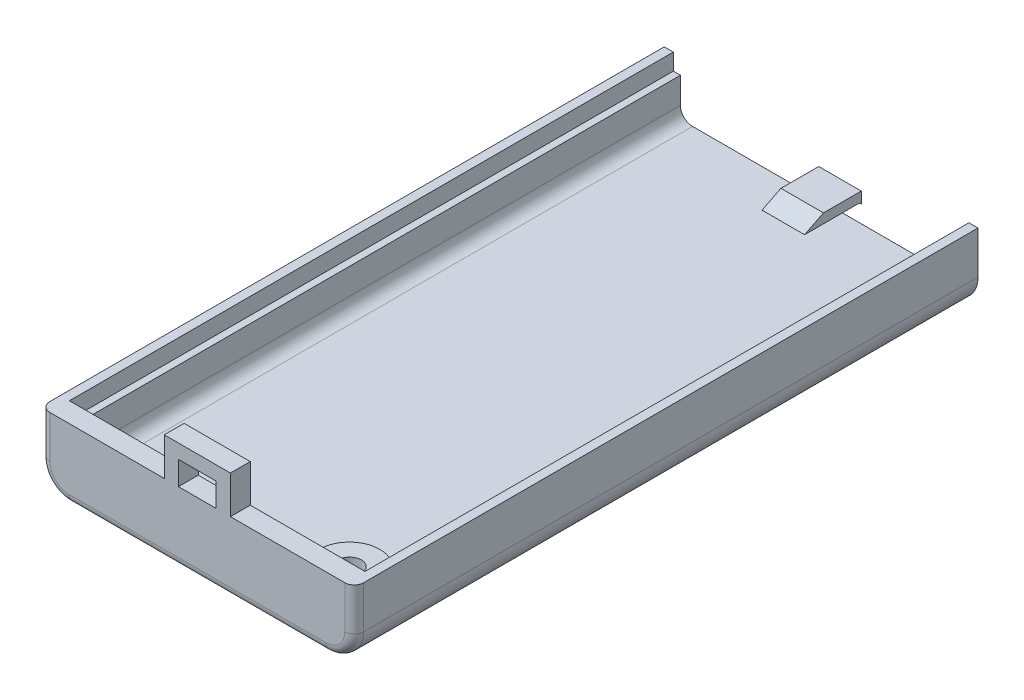
SolidWorks part; units mm, degrees
ref_plane "Plan de face" through (0, 0, 0) normal (0, 0, 1) x (1, 0, 0)
ref_plane "Plan de dessus" through (0, 0, 0) normal (0, 1, 0) x (1, 0, 0)
ref_plane "Plan de droite" through (0, 0, 0) normal (1, 0, 0) x (0, 0, -1)
sketch "Esquisse1" plane through (0, 0, 0) normal (0, 0, 1) x (1, 0, 0)
  line L0 (0, 15.2923) -> (0, -18.7385) construction
  line L1 (-13.6, -7.5) -> (13.6, -7.5)
  line L2 (-16.6, -4.5) -> (-16.6, 0)
  line L3 (16.6, -4.5) -> (16.6, 0)
  arc A0 (16.6, -4.5) -> (13.6, -7.5) centre (13.6, -4.5) cw
  arc A1 (-13.6, -7.5) -> (-16.6, -4.5) centre (-13.6, -4.5) cw
  point P3 (-16.6, -2.25)
  point P12 (16.6, -2.25)
  dimension "D3" = 3
  dimension "D1" = 16.6
  dimension "D2" = 7.5
  dimension "D4" = 16.6
extrude "Extru.-Mince1" add sketch "Esquisse1" along normal blind 32 and the other way blind 32 thin thin type one direction reverse wall 1.71
sketch "Esquisse2" plane through (0, 0, 32) normal (0, 0, 1) x (1, 0, 0)
  line L0 (16.6, -4.5) -> (16.6, 0) construction
  line L1 (-13.6, -7.5) -> (13.6, -7.5) construction
  line L2 (-16.6, 0) -> (-16.6, -4.5) construction
  line L3 (16.6, -4.5) -> (16.6, 0)
  line L4 (-13.6, -7.5) -> (13.6, -7.5)
  line L5 (-16.6, 0) -> (-16.6, -4.5)
  line L6 (-16.6, 0) -> (-3.5, 0)
  line L7 (0, 5.1948) -> (0, -16.7122) construction
  line L9 (-2, 0) -> (2, 0)
  line L10 (-2, 0) -> (-2, 2.5)
  line L11 (3.5, 0) -> (16.6, 0)
  line L12 (-3.5, 0) -> (-3.5, 4)
  line L13 (-3.5, 4) -> (3.5, 4)
  line L14 (3.5, 4) -> (3.5, 0)
  line L15 (-2, 2.5) -> (2, 2.5)
  line L16 (2, 0) -> (2, 2.5)
  arc A0 (13.6, -7.5) -> (16.6, -4.5) centre (13.6, -4.5) ccw construction
  arc A1 (-16.6, -4.5) -> (-13.6, -7.5) centre (-13.6, -4.5) ccw construction
  arc A2 (13.6, -7.5) -> (16.6, -4.5) centre (13.6, -4.5) ccw
  arc A3 (-16.6, -4.5) -> (-13.6, -7.5) centre (-13.6, -4.5) ccw
  dimension "D1" = 7
  dimension "D2" = 4
  dimension "D3" = 4
  dimension "D4" = 2.5
extrude "Boss.-Extru.1" add sketch "Esquisse2" along normal blind 2 and the other way blind 0.1
sketch "Esquisse3" plane through (0, 0, 0) normal (0, 1, 0) x (1, 0, 0)
  line L0 (0, -38.3609) -> (0, 35.8081) construction
  line L1 (-15.64, -31.9) -> (15.64, -31.9)
  line L2 (-15.64, -31.9) -> (-15.64, 34)
  line L3 (-15.64, 34) -> (15.64, 34)
  line L4 (15.64, -31.9) -> (15.64, 34)
  line L6 (14.89, -31.9) -> (3.5, -31.9) construction
  line L7 (-14.89, 32) -> (-14.89, -31.9) construction
  dimension "D1" = 34
  dimension "D2" = 0.75
extrude "Enlèv. mat.-Extru.4" cut sketch "Esquisse3" against normal blind 1.75
sketch "Esquisse4" plane through (0, -5.79, 0) normal (0, 1, 0) x (1, 0, 0)
  line L0 (0, -7.689) -> (0, 39.4106) construction
  line L1 (-13.6, 32) -> (13.6, 32) construction
  line L2 (-2.25, 28) -> (2.25, 28)
  line L3 (-2.25, 28) -> (-2.25, 34)
  line L4 (-2.25, 34) -> (2.25, 34)
  line L5 (2.25, 28) -> (2.25, 34)
  dimension "D1" = 2
  dimension "D2" = 6
  dimension "D3" = 4.5
extrude "Boss.-Extru.2" add sketch "Esquisse4" along normal blind 1
sketch "Esquisse5" plane through (0, 0, 0) normal (1, 0, 0) x (0, 0, -1)
  line L0 (34, -5.79) -> (34, -5.99)
  line L1 (34, -5.99) -> (33.8, -5.79)
  line L2 (32, -5.79) -> (34, -5.79) construction
  line L3 (33.8, -5.79) -> (34, -5.79)
  dimension "D1" = 0.2
  dimension "D2" = 0.2
extrude "Boss.-Extru.3" add sketch "Esquisse5" along normal up to surface and the other way up to surface up to face at (2.25, -5.39, -31.2) other way up to face at (-2.25, -5.39, -31.2)
sketch "Esquisse6" plane through (2.25, 0, 0) normal (1, 0, 0) x (0, 0, -1)
  line L0 (28, -5.79) -> (30, -4.79)
  line L1 (28, -4.79) -> (34, -4.79) construction
  line L2 (30, -4.79) -> (28, -4.79)
  line L3 (28, -4.79) -> (28, -5.79)
  dimension "D1" = 2
extrude "Enlèv. mat.-Extru.5" cut sketch "Esquisse6" against normal up to next
sketch "Esquisse7" plane through (0, -7.5, 0) normal (0, -1, 0) x (1, 0, 0)
  line L0 (-3.25, -24) -> (3.25, -24)
  line L1 (-2.8333, -22.5) -> (2.8333, -22.5)
  line L2 (-2.4167, -21) -> (2.4167, -21)
  line L3 (0, 7.167) -> (0, -38.9677) construction
  line L4 (-13.6, -32) -> (13.6, -32) construction
  line L5 (-2, -19.5) -> (2, -19.5)
  line L6 (-2, -19.5) -> (-3.25, -24) construction
  line L7 (2, -19.5) -> (3.25, -24) construction
  dimension "D1" = 6.5
  dimension "D2" = 8
  dimension "D3" = 1.5
  dimension "D4" = 1.5
  dimension "D5" = 1.5
  dimension "D6" = 4
extrude "Extru.-Mince2" add sketch "Esquisse7" along normal blind 0.2 thin
sketch "Esquisse8" plane through (0, -7.5, 0) normal (0, -1, 0) x (1, 0, 0)
  line L0 (16.6, -32) -> (16.6, 34) construction
  line L2 (-13.6, 34) -> (13.6, 34) construction
  circle A0 centre (9.6, 27.5) radius 2.5
  dimension "D3" = 5
  dimension "D1" = 7
  dimension "D2" = 6.5
extrude "Enlèv. mat.-Extru.6" cut sketch "Esquisse8" against normal through all
sketch "Esquisse9" plane through (0, -5.79, 0) normal (0, 1, 0) x (1, 0, 0)
  circle A0 centre (9.6, -27.5) radius 3.2
  circle A1 centre (9.6, -27.5) radius 1.25
  dimension "D1" = 6.4
  dimension "D2" = 2.5
extrude "Boss.-Extru.4" add sketch "Esquisse9" along normal blind 1
fillet "Congé1" radius 1 5 edges at (-16.6, -2.25, 34) (-15.7213, -6.6213, 34) (16.6, -2.25, 34) (15.7213, -6.6213, 34) (0, -7.5, 34)
